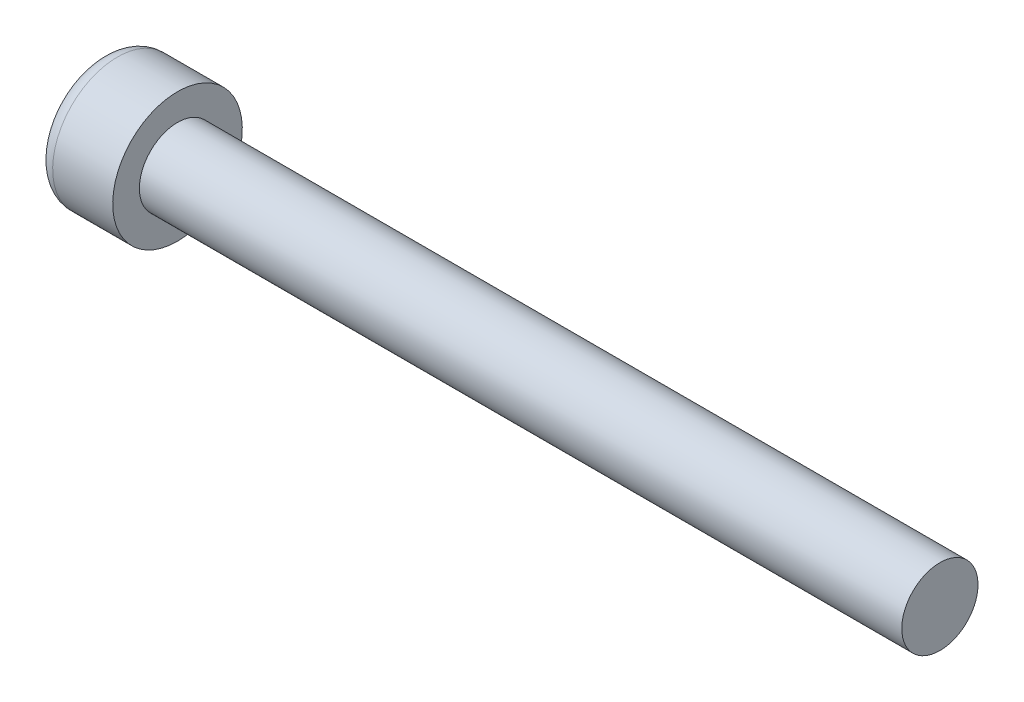
SolidWorks part; units mm, degrees
material "Plain Carbon Steel"
ref_plane "Front Plane" through (0, 0, 0) normal (0, 0, 1) x (1, 0, 0)
ref_plane "Top Plane" through (0, 0, 0) normal (0, 1, 0) x (1, 0, 0)
ref_plane "Right Plane" through (0, 0, 0) normal (1, 0, 0) x (0, 0, -1)
sketch "Sketch1" plane through (0, 0, 0) normal (0, 0, 1) x (1, 0, 0)
  line L0 (0, 0) -> (0, 3.1875)
  line L1 (1.0625, 4.25) -> (5, 4.25)
  line L2 (5, 4.25) -> (5, 2.5)
  line L3 (5, 2.5) -> (55, 2.5)
  line L4 (55, 2.5) -> (55, 0)
  line L5 (55, 0) -> (0, 0) construction
  line L6 (1.0625, 3.1875) -> (1.0625, 2.125) construction
  line L7 (1.0625, 2.125) -> (1.0625, 1.0625) construction
  line L8 (1.0625, 1.0625) -> (1.0625, 0) construction
  line L9 (1.0625, 4.25) -> (1.0625, 3.1875) construction
  line L10 (0, 0) -> (55, 0)
  arc A0 (0, 3.1875) -> (1.0625, 4.25) centre (1.0625, 3.1875) cw
  dimension "D1" = 5
  dimension "D2" = 8.5
  dimension "D3" = 5
  dimension "D4" = 50
revolve "Revolve1" add sketch "Sketch1" angle 360 about L10
sketch "Sketch2" plane through (0, 0, 0) normal (-1, 0, 0) x (0, 0, 1)
  line L1 (0, 2.3094) -> (-2, 1.1547)
  line L2 (-2, 1.1547) -> (-2, -1.1547)
  line L3 (-2, -1.1547) -> (0, -2.3094)
  line L4 (0, -2.3094) -> (2, -1.1547)
  line L5 (2, -1.1547) -> (2, 1.1547)
  line L6 (2, 1.1547) -> (0, 2.3094)
  circle A0 centre (0, 0) radius 2 construction
  dimension "D1" = 4
extrude "Cut-Extrude1" cut sketch "Sketch2" against normal blind 2.5
